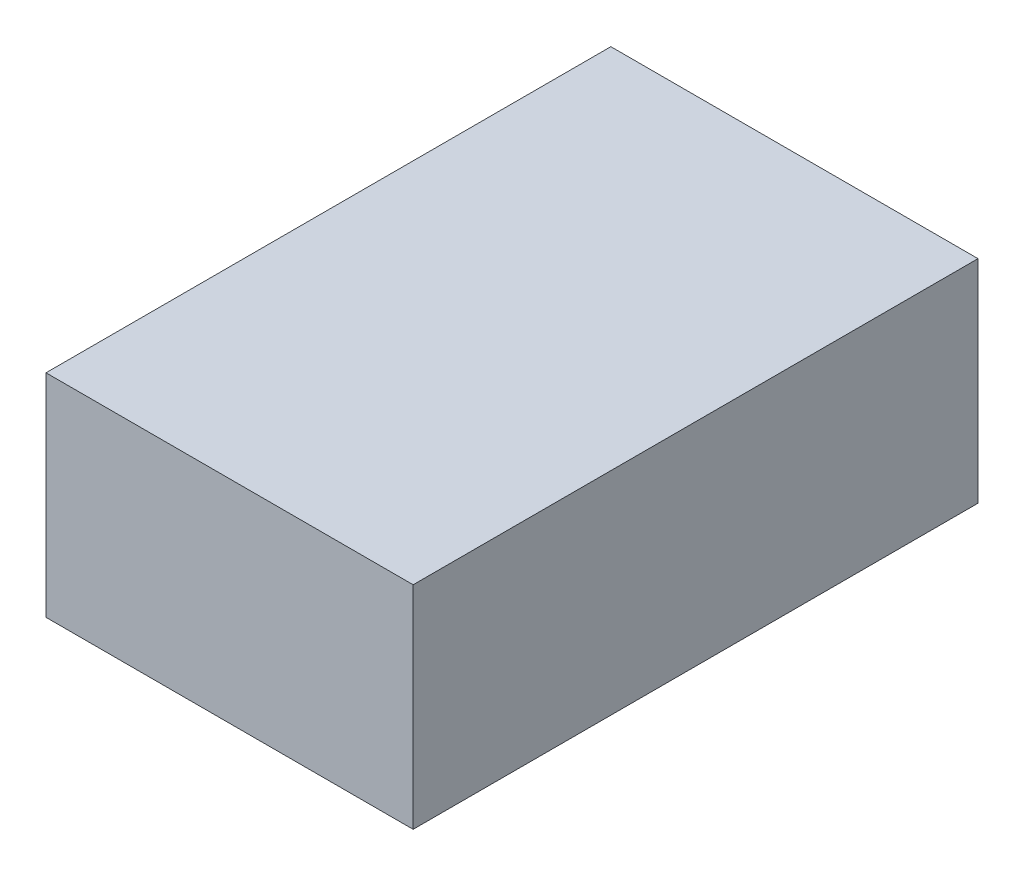
SolidWorks part; units mm, degrees
ref_plane "前视基准面" through (0, 0, 0) normal (0, 0, 1) x (1, 0, 0)
ref_plane "上视基准面" through (0, 0, 0) normal (0, 1, 0) x (1, 0, 0)
ref_plane "右视基准面" through (0, 0, 0) normal (1, 0, 0) x (0, 0, -1)
sketch "草图1" plane through (0, 0, 0) normal (0, 1, 0) x (1, 0, 0)
  line L1 (-17.6981, -18.3417) -> (-15.0981, -18.3417)
  line L2 (-17.6981, -18.3417) -> (-17.6981, -22.3417)
  line L3 (-17.6981, -22.3417) -> (-15.0981, -22.3417)
  line L4 (-15.0981, -18.3417) -> (-15.0981, -22.3417)
  dimension "D1" = 4
  dimension "D2" = 2.6
extrude "凸台-拉伸1" add sketch "草图1" along normal blind 1.5
